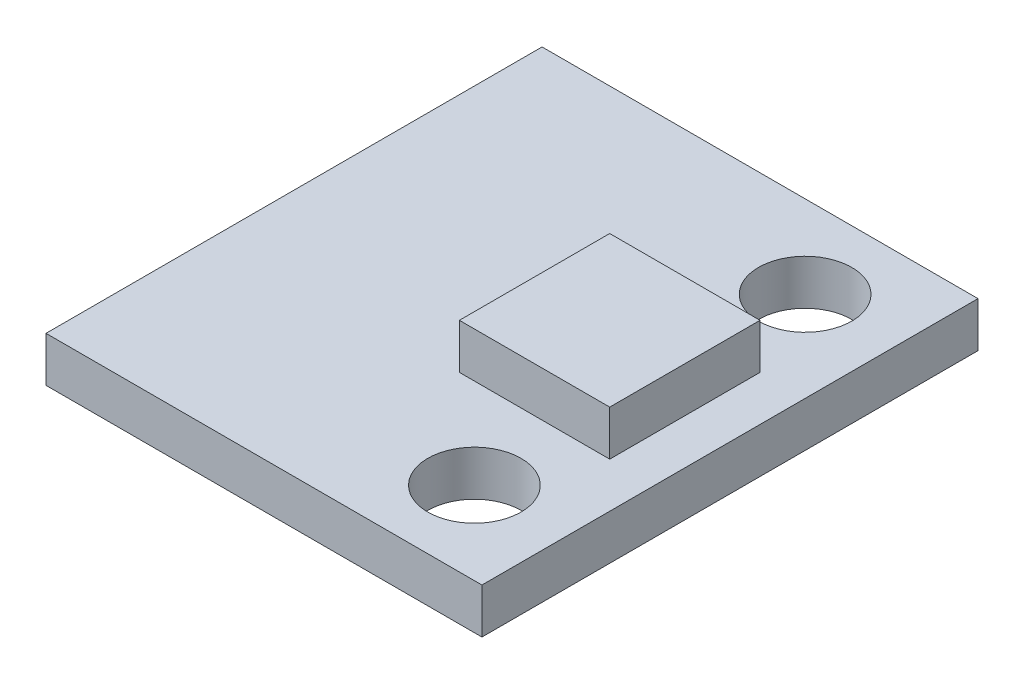
SolidWorks part; units mm, degrees
ref_plane "Front Plane" through (0, 0, 0) normal (0, 0, 1) x (1, 0, 0)
ref_plane "Top Plane" through (0, 0, 0) normal (0, 1, 0) x (1, 0, 0)
ref_plane "Right Plane" through (0, 0, 0) normal (1, 0, 0) x (0, 0, -1)
sketch "Sketch1" plane through (0, 0, 0) normal (0, 1, 0) x (1, 0, 0)
  line L1 (-7.25, -8.25) -> (7.25, -8.25)
  line L2 (-7.25, -8.25) -> (-7.25, 8.25)
  line L3 (-7.25, 8.25) -> (7.25, 8.25)
  line L4 (7.25, -8.25) -> (7.25, 8.25)
  line L5 (-7.25, -8.25) -> (7.25, 8.25) construction
  line L6 (-7.25, 8.25) -> (7.25, -8.25) construction
  point P0 (0, 0)
  dimension "D1" = 14.5
  dimension "D2" = 16.5
extrude "Boss-Extrude1" add sketch "Sketch1" along normal blind 1.5
sketch "Sketch2" plane through (0, 1.5, 0) normal (0, 1, 0) x (1, 0, 0)
  line L0 (-7.25, 0) -> (7.25, 0) construction
  line L1 (-7.25, 8.25) -> (-7.25, -8.25) construction
  line L2 (7.25, -8.25) -> (7.25, 8.25) construction
  circle A0 centre (4.25, 5.5) radius 1.55
  circle A1 centre (4.25, -5.5) radius 1.55
  dimension "D1" = 3.1
  dimension "D2" = 3
  dimension "D3" = 11
extrude "Cut-Extrude1" cut sketch "Sketch2" against normal through all
sketch "Sketch3" plane through (0, 1.5, 0) normal (0, 1, 0) x (1, 0, 0)
  line L0 (-7.25, 0) -> (7.25, 0) construction
  line L1 (-7.25, 8.25) -> (-7.25, -8.25) construction
  line L2 (7.25, -8.25) -> (7.25, 8.25) construction
  line L4 (0.75, -2.5) -> (5.75, -2.5)
  line L5 (0.75, -2.5) -> (0.75, 2.5)
  line L6 (0.75, 2.5) -> (5.75, 2.5)
  line L7 (5.75, -2.5) -> (5.75, 2.5)
  line L8 (0.75, -2.5) -> (5.75, 2.5) construction
  line L9 (0.75, 2.5) -> (5.75, -2.5) construction
  point P6 (3.25, 0)
  dimension "D1" = 5
  dimension "D2" = 5
  dimension "D3" = 4
extrude "Boss-Extrude2" add sketch "Sketch3" along normal blind 1.5
